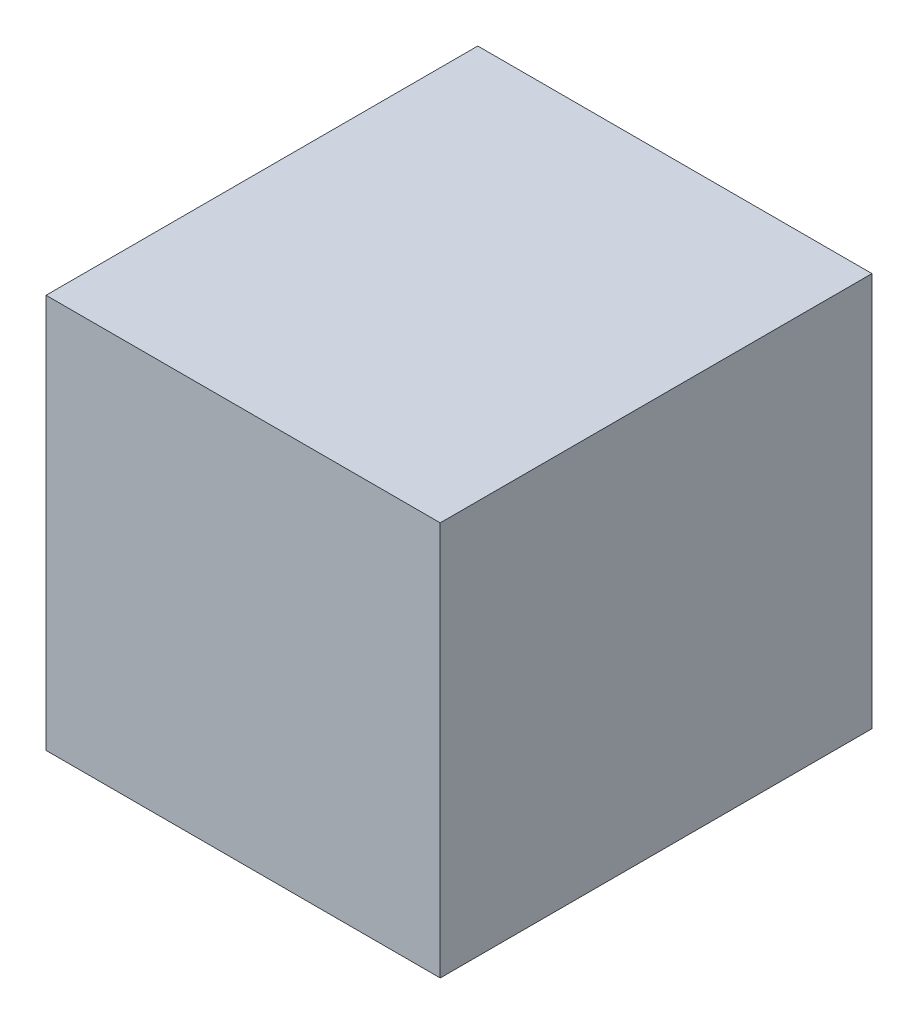
SolidWorks part; units mm, degrees
ref_plane "Plan de face" through (0, 0, 0) normal (0, 0, 1) x (1, 0, 0)
ref_plane "Plan de dessus" through (0, 0, 0) normal (0, 1, 0) x (1, 0, 0)
ref_plane "Plan de droite" through (0, 0, 0) normal (1, 0, 0) x (0, 0, -1)
sketch "Esquisse1" plane through (0, 0, 0) normal (0, 0, 1) x (1, 0, 0)
  line L1 (-52.5, 52.5) -> (52.5, 52.5)
  line L2 (-52.5, 52.5) -> (-52.5, -52.5)
  line L3 (-52.5, -52.5) -> (52.5, -52.5)
  line L4 (52.5, 52.5) -> (52.5, -52.5)
  line L5 (-52.5, 52.5) -> (52.5, -52.5) construction
  line L6 (-52.5, -52.5) -> (52.5, 52.5) construction
  point P0 (0, 0)
  point P5 (0, 0)
  dimension "D1" = 105
  dimension "D2" = 105
extrude "Boss.-Extru.1" add sketch "Esquisse1" along normal blind 115
